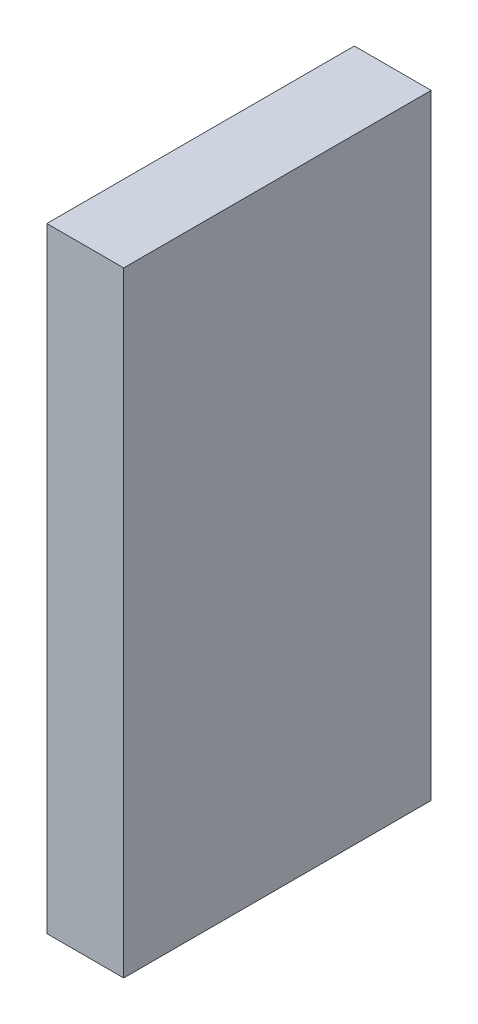
SolidWorks part; units mm, degrees
ref_plane "Front Plane" through (0, 0, 0) normal (0, 0, 1) x (1, 0, 0)
ref_plane "Top Plane" through (0, 0, 0) normal (0, 1, 0) x (1, 0, 0)
ref_plane "Right Plane" through (0, 0, 0) normal (1, 0, 0) x (0, 0, -1)
sketch "Sketch1" plane through (0, 0, 0) normal (1, 0, 0) x (0, 0, -1)
  line L1 (-12.7, 25.4) -> (12.7, 25.4)
  line L2 (-12.7, 25.4) -> (-12.7, -25.4)
  line L3 (-12.7, -25.4) -> (12.7, -25.4)
  line L4 (12.7, 25.4) -> (12.7, -25.4)
  line L5 (-12.7, 25.4) -> (12.7, -25.4) construction
  line L6 (-12.7, -25.4) -> (12.7, 25.4) construction
  point P0 (0, 0)
  dimension "D1" = 25.4
  dimension "D2" = 50.8
extrude "Boss-Extrude1" add sketch "Sketch1" along normal mid plane 6.35
